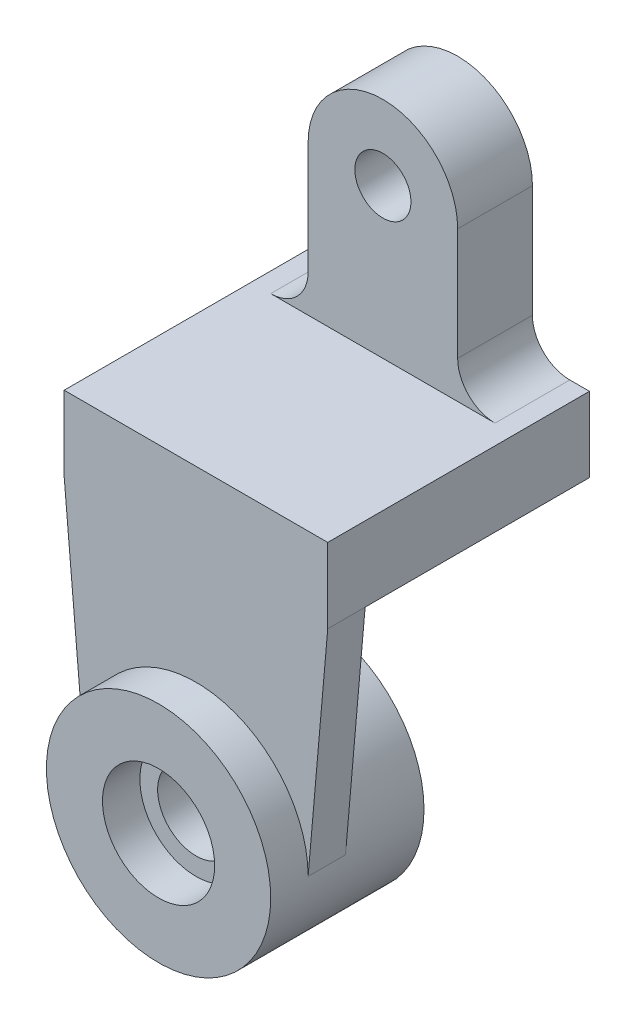
SolidWorks part; units mm, degrees
ref_plane "Front Plane" through (0, 0, 0) normal (0, 0, 1) x (1, 0, 0)
ref_plane "Top Plane" through (0, 0, 0) normal (0, 1, 0) x (1, 0, 0)
ref_plane "Right Plane" through (0, 0, 0) normal (1, 0, 0) x (0, 0, -1)
sketch "Sketch1" plane through (0, 0, 0) normal (0, 0, 1) x (1, 0, 0)
  circle A0 centre (0, 0) radius 762
  circle A1 centre (0, 0) radius 381
extrude "Boss-Extrude1" add sketch "Sketch1" against normal blind 533.4
sketch "Sketch3" plane through (0, 0, 0) normal (0, 0, 1) x (1, 0, 0)
  line L1 (-895.35, 2032) -> (-895.35, 1524)
  line L2 (895.35, 2032) -> (895.35, 1524)
  line L3 (-895.35, 2032) -> (895.35, 2032)
  line L4 (895.35, 1524) -> (762, 0)
  line L5 (-895.35, 1524) -> (-762, 0)
  arc A0 (-762, 0) -> (762, 0) centre (0, 0) ccw
  circle A1 centre (0, 0) radius 261.112
  circle A4 centre (0, 0) radius 381 construction
  dimension "D1" = 895.35
  dimension "D2" = 522.224
  dimension "D3" = 1524
  dimension "D5" = 1524
  dimension "D6" = 2032
extrude "Boss-Extrude3" add sketch "Sketch3" along normal blind 254 contours L2 L4 A0 L5 L1 L3
sketch "Sketch6" plane through (0, 0, 254) normal (0, 0, 1) x (1, 0, 0)
  circle A0 centre (0, 0) radius 260.35
extrude "Cut-Extrude1" cut sketch "Sketch6" against normal blind 254
sketch "Sketch7" plane through (0, 0, 254) normal (0, 0, 1) x (1, 0, 0)
  circle A0 centre (0, 0) radius 381
  circle A1 centre (0, 0) radius 762
extrude "Boss-Extrude4" add sketch "Sketch7" along normal blind 254
sketch "Sketch8" plane through (0, 0, 0) normal (0, 0, -1) x (-1, 0, 0)
  line L0 (-895.35, 2032) -> (-895.35, 1524)
  line L1 (-895.35, 2032) -> (-895.35, 1524) construction
  line L2 (-895.35, 1524) -> (895.35, 1524)
  line L3 (895.35, 2032) -> (895.35, 1524) construction
  line L4 (895.35, 1524) -> (895.35, 2032)
  line L5 (895.35, 2032) -> (-895.35, 2032)
extrude "Boss-Extrude5" add sketch "Sketch8" along normal blind 1524
sketch "Sketch9" plane through (0, 0, -1524) normal (0, 0, -1) x (-1, 0, 0)
  line L0 (0, 2032) -> (0, 3048) construction
  line L1 (895.35, 2032) -> (-895.35, 2032) construction
  line L2 (-508, 3048) -> (-508, 2286)
  line L3 (508, 3048) -> (508, 2286)
  line L4 (-895.35, 2032) -> (-895.35, 1524) construction
  line L5 (-762, 2032) -> (-895.35, 2032)
  line L7 (-895.35, 2032) -> (-895.35, 1524)
  line L9 (-895.35, 1524) -> (895.35, 1524) construction
  line L10 (-895.35, 1524) -> (895.35, 1524) construction
  line L11 (-895.35, 1524) -> (895.35, 1524)
  line L12 (895.35, 1524) -> (895.35, 2032)
  line L13 (895.35, 1524) -> (895.35, 2032) construction
  line L14 (895.35, 2032) -> (762, 2032)
  circle A0 centre (0, 3048) radius 190.5
  arc A1 (508, 3048) -> (-508, 3048) centre (0, 3048) ccw
  arc A2 (-762, 2032) -> (-508, 2286) centre (-762, 2286) ccw
  arc A3 (508, 2286) -> (762, 2032) centre (762, 2286) ccw
  dimension "D1" = 508
  dimension "D2" = 1016
  dimension "D3" = 381
  dimension "D5" = 508
  dimension "D4" = 1016
extrude "Boss-Extrude6" add sketch "Sketch9" against normal blind 508 contours A1 L2 A2 L5 L7 L11 L12 L14 A3 L3
sketch "Sketch10" plane through (0, 0, -1524) normal (0, 0, -1) x (-1, 0, 0)
  circle A0 centre (0, 3048) radius 190.5
extrude "Cut-Extrude2" cut sketch "Sketch10" against normal blind 508
